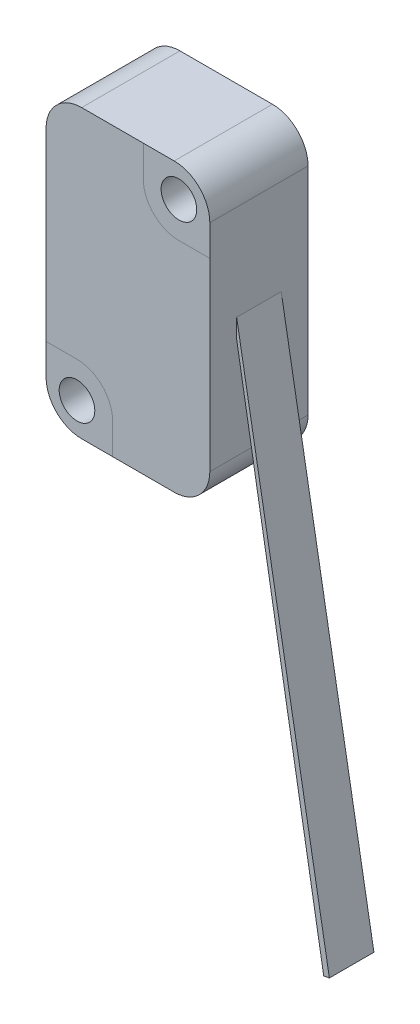
SolidWorks part; units mm, degrees
ref_plane "Front Plane" through (0, 0, 0) normal (0, 0, 1) x (1, 0, 0)
ref_plane "Top Plane" through (0, 0, 0) normal (0, 1, 0) x (1, 0, 0)
ref_plane "Right Plane" through (0, 0, 0) normal (1, 0, 0) x (0, 0, -1)
sketch "Sketch1" plane through (0, 0, 0) normal (0, 0, 1) x (1, 0, 0)
  line L1 (-7.9375, -13.9065) -> (7.9375, -13.9065)
  line L2 (-7.9375, -13.9065) -> (-7.9375, 13.9065)
  line L3 (-7.9375, 13.9065) -> (7.9375, 13.9065)
  line L4 (7.9375, -13.9065) -> (7.9375, 13.9065)
  line L5 (-7.9375, -13.9065) -> (7.9375, 13.9065) construction
  line L6 (-7.9375, 13.9065) -> (7.9375, -13.9065) construction
  point P0 (0, 0)
  dimension "D1" = 15.875
  dimension "D2" = 27.813
extrude "Boss-Extrude1" add sketch "Sketch1" along normal mid plane 9.525 contours L3 L4 L1 L2
sketch "Sketch2" plane through (0, 0, 0) normal (0, 0, 1) x (1, 0, 0)
  line L0 (7.9375, 1.2065) -> (16.9264, -49.7723)
  line L1 (7.9375, -13.9065) -> (7.9375, 13.9065) construction
  line L2 (16.9264, -49.7723) -> (16.3761, -49.8693)
  line L3 (16.3761, -49.8693) -> (7.9375, -0.655)
  line L5 (7.9375, -0.655) -> (7.9375, 1.2065)
  line L8 (-7.9375, 13.9065) -> (-7.9375, -13.9065)
  line L9 (-7.9375, -13.9065) -> (7.9375, -13.9065)
  line L10 (7.9375, -13.9065) -> (7.9375, 13.9065)
  line L11 (7.9375, 13.9065) -> (-7.9375, 13.9065)
  line L14 (7.9375, 1.2065) -> (7.9375, 13.9065)
  dimension "D1" = 12.7
  dimension "D2" = 0.5588
  dimension "D3" = 10
  dimension "D5" = 51.7652
  dimension "D4" = 0
extrude "Boss-Extrude2" add sketch "Sketch2" along normal mid plane 4.318 contours L0 L2 L3 L5
hole_wizard "#29 (0.136) Diameter Hole1" positions "Sketch3" profile "Sketch4" hole size "#29" standard "ANSI Inch" end condition through all
sketch "Sketch3" plane through (0, 0, 4.7625) normal (0, 0, 1) x (1, 0, 0)
  line L1 (-7.9375, -13.9065) -> (7.9375, -13.9065) construction
  line L2 (-7.9375, -13.9065) -> (-7.9375, 13.9065) construction
  circle A0 centre (-4.9403, -10.9093) radius 1.7272
  point P2 (-4.9403, -10.9093)
  point P23 (4.9403, 10.9093)
  dimension "D2" = 3.4544
  dimension "D1" = 2.9972
  dimension "D3" = 2.9972
sketch "Sketch4" plane through (-4.9403, -10.9093, 4.7625) normal (1, 0, 0) x (0, -1, 0)
  line L0 (0, 0) -> (0, 9.525)
  line L1 (0, 9.525) -> (1.7272, 9.525)
  line L2 (1.7272, 9.525) -> (1.7272, 0)
  line L5 (1.7272, 0) -> (0, 0)
  line L11 (0, -6.35) -> (0, 107.95) construction
  dimension "Thru Hole Dia." = 3.4544
  dimension "Thru Hole Depth" = 9.525
fillet "Fillet1" radius 3.4544 4 edges at (7.9375, -13.9065, 0) (-7.9375, -13.9065, 0) (7.9375, 13.9065, 0) (-7.9375, 13.9065, 0)
sketch "Sketch5" plane through (0, 0, 4.7625) normal (0, 0, 1) x (1, 0, 0)
  line L0 (1.4859, 13.9065) -> (1.4859, 10.9093)
  line L1 (-4.4831, 13.9065) -> (4.4831, 13.9065) construction
  line L2 (7.9375, 7.4549) -> (4.9403, 7.4549)
  line L3 (7.9375, -10.4521) -> (7.9375, 10.4521) construction
  line L4 (1.4859, 13.9065) -> (4.4831, 13.9065)
  line L5 (7.9375, 7.4549) -> (7.9375, 10.4521)
  line L6 (5.2388, 0) -> (-5.2388, 0) construction
  line L7 (7.9375, -10.4521) -> (7.9375, 7.4549) construction
  line L8 (7.9375, -7.4549) -> (7.9375, -10.4521) construction
  line L9 (1.4859, -13.9065) -> (4.4831, -13.9065) construction
  line L10 (7.9375, -7.4549) -> (4.9403, -7.4549) construction
  line L11 (1.4859, -13.9065) -> (1.4859, -10.9093) construction
  line L12 (0, -5.2388) -> (0, 5.2388) construction
  line L13 (-1.4859, -13.9065) -> (-1.4859, -10.9093)
  line L14 (-7.9375, -7.4549) -> (-4.9403, -7.4549)
  line L15 (-1.4859, -13.9065) -> (-4.4831, -13.9065)
  line L16 (-7.9375, -7.4549) -> (-7.9375, -10.4521)
  arc A0 (1.4859, 10.9093) -> (4.9403, 7.4549) centre (4.9403, 10.9093) ccw
  arc A1 (7.9375, 10.4521) -> (4.4831, 13.9065) centre (4.4831, 10.4521) ccw construction
  circle A2 centre (4.9403, 10.9093) radius 1.7272 construction
  arc A3 (7.9375, 10.4521) -> (4.4831, 13.9065) centre (4.4831, 10.4521) ccw
  arc A4 (7.9375, -10.4521) -> (4.4831, -13.9065) centre (4.4831, -10.4521) cw construction
  arc A5 (1.4859, -10.9093) -> (4.9403, -7.4549) centre (4.9403, -10.9093) cw construction
  arc A6 (-1.4859, -10.9093) -> (-4.9403, -7.4549) centre (-4.9403, -10.9093) ccw
  arc A7 (-7.9375, -10.4521) -> (-4.4831, -13.9065) centre (-4.4831, -10.4521) ccw
split line "Split Line1"
